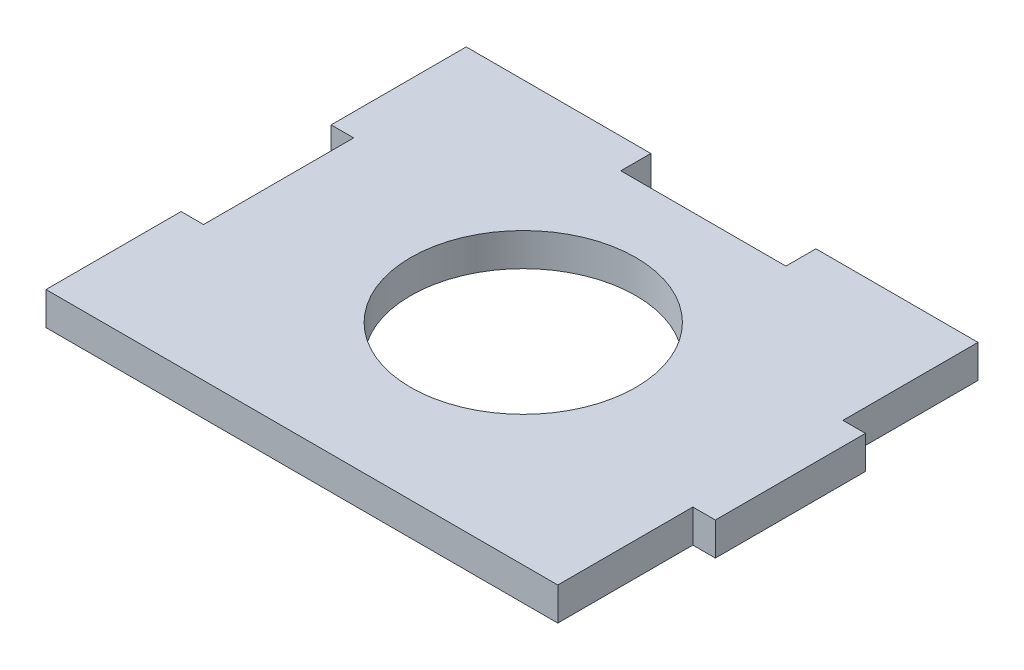
SolidWorks part; units mm, degrees
material "cardboard"
ref_plane "Front Plane" through (0, 0, 0) normal (0, 0, 1) x (1, 0, 0)
ref_plane "Top Plane" through (0, 0, 0) normal (0, 1, 0) x (1, 0, 0)
ref_plane "Right Plane" through (0, 0, 0) normal (1, 0, 0) x (0, 0, -1)
sketch "Sketch1" plane through (0, 0, 0) normal (0, 1, 0) x (1, 0, 0)
  line L0 (-131.9046, 127.7058) -> (-120.9046, 127.7058)
  line L1 (-121.9046, 123.7058) -> (-121.9046, 107.7058)
  line L2 (-62.1046, 123.7058) -> (-62.1046, 107.7058)
  line L3 (-119.5046, 107.7058) -> (-121.9046, 107.7058)
  line L4 (-133.3046, 123.7058) -> (-130.9046, 123.7058)
  line L5 (-133.3046, 123.7058) -> (-133.3046, 107.7058)
  line L6 (-133.3046, 107.7058) -> (-130.9046, 107.7058)
  line L7 (-130.9046, 123.7058) -> (-130.9046, 107.7058)
  line L8 (-119.5046, 123.7058) -> (-119.5046, 107.7058)
  line L9 (-119.5046, 123.7058) -> (-121.9046, 123.7058)
  line L10 (-59.7046, 123.7058) -> (-59.7046, 107.7058)
  line L11 (-96.3046, 127.7058) -> (-85.3046, 127.7058)
  line L12 (-62.1046, 123.7058) -> (-59.7046, 123.7058)
  line L13 (-62.1046, 107.7058) -> (-59.7046, 107.7058)
  line L14 (-50.7046, 123.7058) -> (-50.7046, 107.7058)
  line L15 (-48.3046, 123.7058) -> (-50.7046, 123.7058)
  line L16 (-48.3046, 123.7058) -> (-48.3046, 107.7058)
  line L17 (-48.3046, 107.7058) -> (-50.7046, 107.7058)
  line L18 (9.0954, 123.7058) -> (9.0954, 107.7058)
  line L19 (11.4954, 123.7058) -> (11.4954, 107.7058)
  line L20 (9.0954, 123.7058) -> (11.4954, 123.7058)
  line L21 (9.0954, 107.7058) -> (11.4954, 107.7058)
  line L22 (20.4954, 123.7058) -> (20.4954, 107.7058)
  line L23 (22.8954, 123.7058) -> (20.4954, 123.7058)
  line L24 (22.8954, 123.7058) -> (22.8954, 107.7058)
  line L25 (22.8954, 107.7058) -> (20.4954, 107.7058)
  line L26 (80.2954, 123.7058) -> (80.2954, 107.7058)
  line L27 (82.6954, 123.7058) -> (82.6954, 107.7058)
  line L28 (-60.7046, 127.7058) -> (-49.7046, 127.7058)
  line L29 (80.2954, 123.7058) -> (82.6954, 123.7058)
  line L30 (80.2954, 107.7058) -> (82.6954, 107.7058)
  line L31 (91.6954, 123.7058) -> (91.6954, 107.7058)
  line L32 (57.0954, 129.7058) -> (81.6954, 129.7058)
  line L33 (94.0954, 123.7058) -> (91.6954, 123.7058)
  line L34 (94.0954, 123.7058) -> (94.0954, 107.7058)
  line L35 (94.0954, 107.7058) -> (91.6954, 107.7058)
  line L36 (63.1525, 37.6692) -> (69.5684, 31.2534)
  line L37 (83.0553, 17.7664) -> (85.0352, 19.7463)
  line L38 (63.1525, 37.6692) -> (65.1324, 39.6491)
  line L39 (76.6394, 24.1823) -> (83.0553, 17.7664)
  line L40 (83.0553, -85.0845) -> (76.6394, -91.5004)
  line L41 (83.0553, -85.0845) -> (85.0352, -87.0644)
  line L42 (85.0352, -87.0644) -> (65.1324, -106.9672)
  line L43 (63.1525, -104.9873) -> (65.1324, -106.9672)
  line L44 (69.5684, -98.5714) -> (63.1525, -104.9873)
  line L45 (-39.6984, -104.9873) -> (-46.1143, -98.5714)
  line L46 (-39.6984, -104.9873) -> (-41.6783, -106.9672)
  line L47 (-41.6783, -106.9672) -> (-61.5811, -87.0644)
  line L48 (-59.6012, -85.0845) -> (-61.5811, -87.0644)
  line L49 (-53.1854, -91.5004) -> (-59.6012, -85.0845)
  line L50 (-25.1046, 127.7058) -> (-14.1046, 127.7058)
  line L51 (10.4954, 127.7058) -> (21.4954, 127.7058)
  line L52 (46.0954, 127.7058) -> (57.0954, 127.7058)
  line L53 (81.6954, 127.7058) -> (92.6954, 127.7058)
  line L54 (117.2954, 127.7058) -> (128.2954, 127.7058)
  line L55 (-36.375, -101.6639) -> (-34.3056, -103.7333)
  line L56 (-5.9695, -75.501) -> (-3.9, -77.5704)
  line L57 (-56.2778, -81.7611) -> (-58.0456, -83.5289)
  line L58 (-36.375, -101.6639) -> (-38.1428, -103.4317)
  line L59 (-32.1843, -49.2861) -> (-58.3473, -75.4491)
  line L60 (-58.3473, -79.6917) -> (-56.2778, -81.7611)
  line L61 (-3.9, -77.5704) -> (-30.063, -103.7333)
  line L62 (-32.1843, -49.2861) -> (-30.1149, -51.3555)
  line L63 (-144.2046, 129.7058) -> (-131.9046, 129.7058)
  line L64 (-55.5889, 82.4075) -> (-55.5889, 87.4075)
  line L65 (-65.5889, 82.4075) -> (-65.5889, 87.4075)
  line L66 (-35.039, 73.8955) -> (-31.5034, 77.431)
  line L67 (-27.9679, 66.8244) -> (-24.4324, 70.3599)
  line L68 (-19.4559, 46.2745) -> (-14.4559, 46.2745)
  line L69 (-19.4559, 36.2745) -> (-14.4559, 36.2745)
  line L70 (-27.9679, 15.7246) -> (-24.4324, 12.189)
  line L71 (-35.039, 8.6535) -> (-31.5034, 5.118)
  line L72 (-55.5889, 0.1414) -> (-55.5889, -4.8586)
  line L73 (-65.5889, 0.1414) -> (-65.5889, -4.8586)
  line L74 (-86.1388, 8.6535) -> (-89.6743, 5.118)
  line L75 (61.5969, 36.1136) -> (68.0127, 29.6977)
  line L76 (75.0838, 22.6267) -> (81.4997, 16.2108)
  line L77 (75.0838, 22.6267) -> (76.6394, 24.1823)
  line L78 (68.0127, 29.6977) -> (69.5684, 31.2534)
  line L79 (29.8004, -77.2921) -> (32.6289, -74.4636)
  line L80 (55.3601, -15.5856) -> (52.5316, -12.7572)
  line L81 (-144.2046, 129.7058) -> (-144.2046, 119.7058)
  line L82 (-6.3464, 9.974) -> (-31.906, -15.5856)
  line L83 (-144.2046, 101.7058) -> (-110.1046, 101.7058)
  line L84 (-93.2099, 15.7246) -> (-96.7454, 12.189)
  line L85 (-108.6046, 129.7058) -> (-108.6046, 120.7058)
  line L86 (65.1324, 39.6491) -> (85.0352, 19.7463)
  line L87 (-22.6903, -48.1735) -> (-2.7875, -68.0763)
  line L88 (-22.6903, -48.1735) -> (-25.8722, -51.3555)
  line L89 (-2.7875, -68.0763) -> (-5.9695, -71.2583)
  line L90 (-31.906, -15.5856) -> (-66.906, -15.5856)
  line L91 (-81.906, -30.5856) -> (-81.906, -36.7324)
  line L92 (-66.906, -51.7324) -> (-34.6306, -51.7324)
  line L93 (-111.9046, 106.7058) -> (-114.4046, 106.7058)
  line L94 (-140.9046, 126.7058) -> (-138.4046, 126.7058)
  line L95 (-140.9046, 126.7058) -> (-140.9046, 106.7058)
  line L96 (-140.9046, 106.7058) -> (-138.4046, 106.7058)
  line L97 (-138.4046, 126.7058) -> (-138.4046, 106.7058)
  line L98 (-114.4046, 126.7058) -> (-114.4046, 106.7058)
  line L99 (29.8004, 9.974) -> (29.8004, 44.974)
  line L100 (14.8004, 59.974) -> (8.6536, 59.974)
  line L101 (-6.3464, 44.974) -> (-6.3464, 9.974)
  line L102 (-111.9046, 126.7058) -> (-114.4046, 126.7058)
  line L103 (-111.9046, 126.7058) -> (-111.9046, 106.7058)
  line L104 (-132.4046, 101.7058) -> (-132.4046, 97.7058)
  line L105 (-132.4046, 97.7058) -> (-120.4046, 97.7058)
  line L106 (-120.4046, 97.7058) -> (-120.4046, 101.7058)
  line L107 (-108.6046, 129.7058) -> (-108.6046, 120.7058)
  line L108 (55.3601, -51.7324) -> (90.3601, -51.7324)
  line L109 (105.3601, -36.7324) -> (105.3601, -30.5856)
  line L110 (90.3601, -15.5856) -> (55.3601, -15.5856)
  line L111 (-108.6046, 101.7058) -> (-74.5046, 101.7058)
  line L112 (-73.0046, 120.7058) -> (-73.0046, 110.7058)
  line L113 (21.4954, 129.7058) -> (46.0954, 129.7058)
  line L114 (-73.0046, 120.7058) -> (-73.0046, 110.7058)
  line L115 (-61.2046, 101.7058) -> (-37.4046, 101.7058)
  line L116 (-37.4046, 129.7058) -> (-37.4046, 101.7058)
  line L117 (-6.3464, -80.0167) -> (-6.3464, -112.2921)
  line L118 (8.6536, -127.2921) -> (14.8004, -127.2921)
  line L119 (29.8004, -112.2921) -> (29.8004, -77.2921)
  line L120 (-14.1046, 129.7058) -> (10.4954, 129.7058)
  line L121 (-37.4046, 129.7058) -> (-37.4046, 101.7058)
  line L122 (-37.4046, 101.7058) -> (-1.8046, 101.7058)
  line L123 (-1.8046, 129.7058) -> (-1.8046, 101.7058)
  line L124 (-49.7046, 129.7058) -> (-25.1046, 129.7058)
  line L125 (-1.8046, 129.7058) -> (-1.8046, 101.7058)
  line L126 (52.5316, -54.5609) -> (55.3601, -51.7324)
  line L127 (26.2415, -68.0763) -> (46.1443, -48.1735)
  line L128 (81.4997, -83.5289) -> (75.0838, -89.9447)
  line L129 (46.1443, -48.1735) -> (81.4997, -83.5289)
  line L130 (75.0838, -89.9447) -> (76.6394, -91.5004)
  line L131 (78.6193, -93.4803) -> (71.5483, -100.5513)
  line L132 (26.2415, -68.0763) -> (61.5969, -103.4317)
  line L133 (68.0127, -97.0158) -> (69.5684, -98.5714)
  line L134 (68.0127, -97.0158) -> (61.5969, -103.4317)
  line L135 (-38.1428, -103.4317) -> (-44.5587, -97.0158)
  line L136 (-44.5587, -97.0158) -> (-46.1143, -98.5714)
  line L137 (32.6289, 7.1456) -> (29.8004, 9.974)
  line L138 (-101.7219, 36.2745) -> (-106.7219, 36.2745)
  line L139 (46.1443, -19.1445) -> (26.2415, 0.7582)
  line L140 (46.1443, -19.1445) -> (81.4997, 16.2108)
  line L141 (26.2415, 0.7582) -> (61.5969, 36.1136)
  line L142 (-48.0942, -100.5513) -> (-55.1653, -93.4803)
  line L143 (-51.6297, -89.9447) -> (-53.1854, -91.5004)
  line L144 (-51.6297, -89.9447) -> (-58.0456, -83.5289)
  line L145 (-65.5889, 82.4075) -> (-77.6267, 82.4075)
  line L146 (-77.6267, 82.4075) -> (-86.1388, 73.8955)
  line L147 (-1.8046, 101.7058) -> (33.7954, 101.7058)
  line L148 (33.7954, 129.7058) -> (33.7954, 101.7058)
  line L149 (-85.3046, 129.7058) -> (-74.5046, 129.7058)
  line L150 (33.7954, 129.7058) -> (33.7954, 101.7058)
  line L151 (33.7954, 101.7058) -> (69.3954, 101.7058)
  line L152 (69.3954, 129.7058) -> (69.3954, 101.7058)
  line L153 (-108.6046, 129.7058) -> (-96.3046, 129.7058)
  line L154 (69.3954, 129.7058) -> (69.3954, 101.7058)
  line L155 (69.3954, 101.7058) -> (104.9954, 101.7058)
  line L156 (104.9954, 129.7058) -> (104.9954, 101.7058)
  line L157 (128.2954, 129.7058) -> (140.5954, 129.7058)
  line L158 (104.9954, 129.7058) -> (104.9954, 101.7058)
  line L159 (104.9954, 101.7058) -> (140.5954, 101.7058)
  line L160 (140.5954, 129.7058) -> (140.5954, 119.7058)
  line L161 (-69.7046, 126.7058) -> (-67.2046, 126.7058)
  line L162 (-69.7046, 126.7058) -> (-69.7046, 106.7058)
  line L163 (-69.7046, 106.7058) -> (-67.2046, 106.7058)
  line L164 (-67.2046, 126.7058) -> (-67.2046, 106.7058)
  line L165 (-43.2046, 126.7058) -> (-43.2046, 106.7058)
  line L166 (-40.7046, 106.7058) -> (-43.2046, 106.7058)
  line L167 (-40.7046, 126.7058) -> (-40.7046, 106.7058)
  line L168 (-40.7046, 126.7058) -> (-43.2046, 126.7058)
  line L169 (-61.2046, 101.7058) -> (-61.2046, 97.7058)
  line L170 (-61.2046, 97.7058) -> (-49.2046, 97.7058)
  line L171 (-49.2046, 97.7058) -> (-49.2046, 101.7058)
  line L172 (1.4954, 126.7058) -> (3.9954, 126.7058)
  line L173 (1.4954, 126.7058) -> (1.4954, 106.7058)
  line L174 (1.4954, 106.7058) -> (3.9954, 106.7058)
  line L175 (3.9954, 126.7058) -> (3.9954, 106.7058)
  line L176 (27.9954, 126.7058) -> (27.9954, 106.7058)
  line L177 (30.4954, 106.7058) -> (27.9954, 106.7058)
  line L178 (30.4954, 126.7058) -> (30.4954, 106.7058)
  line L179 (30.4954, 126.7058) -> (27.9954, 126.7058)
  line L180 (9.9954, 101.7058) -> (9.9954, 97.7058)
  line L181 (9.9954, 97.7058) -> (21.9954, 97.7058)
  line L182 (21.9954, 97.7058) -> (21.9954, 101.7058)
  line L183 (72.6954, 126.7058) -> (75.1954, 126.7058)
  line L184 (72.6954, 126.7058) -> (72.6954, 106.7058)
  line L185 (72.6954, 106.7058) -> (75.1954, 106.7058)
  line L186 (75.1954, 126.7058) -> (75.1954, 106.7058)
  line L187 (99.1954, 126.7058) -> (99.1954, 106.7058)
  line L188 (101.6954, 106.7058) -> (99.1954, 106.7058)
  line L189 (101.6954, 126.7058) -> (101.6954, 106.7058)
  line L190 (101.6954, 126.7058) -> (99.1954, 126.7058)
  line L191 (81.1954, 101.7058) -> (81.1954, 97.7058)
  line L192 (81.1954, 97.7058) -> (93.1954, 97.7058)
  line L193 (93.1954, 97.7058) -> (93.1954, 101.7058)
  line L194 (-132.4046, 100.7058) -> (-128.4046, 100.7058)
  line L195 (-128.4046, 100.7058) -> (-128.4046, 102.7058)
  line L196 (-128.4046, 102.7058) -> (-124.4046, 102.7058)
  line L197 (-124.4046, 102.7058) -> (-124.4046, 100.7058)
  line L198 (-124.4046, 100.7058) -> (-120.4046, 100.7058)
  line L199 (-61.2046, 100.7058) -> (-57.2046, 100.7058)
  line L200 (-57.2046, 100.7058) -> (-57.2046, 102.7058)
  line L201 (-57.2046, 102.7058) -> (-53.2046, 102.7058)
  line L202 (-53.2046, 102.7058) -> (-53.2046, 100.7058)
  line L203 (-53.2046, 100.7058) -> (-49.2046, 100.7058)
  line L204 (9.9954, 100.7058) -> (13.9954, 100.7058)
  line L205 (13.9954, 100.7058) -> (13.9954, 102.7058)
  line L206 (13.9954, 102.7058) -> (17.9954, 102.7058)
  line L207 (27.6557, 2.1725) -> (34.0197, -4.1915)
  line L208 (34.0197, -4.1915) -> (31.1913, -7.0199)
  line L209 (31.1913, -7.0199) -> (38.3661, -14.1948)
  line L210 (38.3661, -14.1948) -> (41.1946, -11.3664)
  line L211 (41.1946, -11.3664) -> (47.5585, -17.7303)
  line L212 (47.5585, -49.5878) -> (41.1946, -55.9517)
  line L213 (41.1946, -55.9517) -> (38.3661, -53.1233)
  line L214 (38.3661, -53.1233) -> (31.1913, -60.2982)
  line L215 (31.1913, -60.2982) -> (34.0197, -63.1266)
  line L216 (34.0197, -63.1266) -> (27.6557, -69.4905)
  line L217 (-4.2017, -69.4905) -> (-10.5656, -63.1266)
  line L218 (-10.5656, -63.1266) -> (-7.7372, -60.2982)
  line L219 (-7.7372, -60.2982) -> (-14.9121, -53.1233)
  line L220 (-14.9121, -53.1233) -> (-17.7405, -55.9517)
  line L221 (-17.7405, -55.9517) -> (-24.1045, -49.5878)
  line L222 (-89.6743, 77.431) -> (-96.7454, 70.3599)
  line L223 (-93.2099, 66.8244) -> (-101.7219, 58.3123)
  line L224 (-101.7219, 58.3123) -> (-101.7219, 46.2745)
  line L225 (-106.7219, 46.2745) -> (-106.7219, 36.2745)
  line L226 (-101.7219, 36.2745) -> (-101.7219, 24.2366)
  line L227 (-101.7219, 24.2366) -> (-93.2099, 15.7246)
  line L228 (-96.7454, 12.189) -> (-89.6743, 5.118)
  line L229 (-86.1388, 8.6535) -> (-77.6267, 0.1414)
  line L230 (-77.6267, 0.1414) -> (-65.5889, 0.1414)
  line L231 (-65.5889, -4.8586) -> (-55.5889, -4.8586)
  line L232 (-55.5889, 0.1414) -> (-43.551, 0.1414)
  line L233 (-43.551, 0.1414) -> (-35.039, 8.6535)
  line L234 (-31.5034, 5.118) -> (-24.4324, 12.189)
  line L235 (-27.9679, 15.7246) -> (-19.4559, 24.2366)
  line L236 (-19.4559, 24.2366) -> (-19.4559, 36.2745)
  line L237 (-14.4559, 36.2745) -> (-14.4559, 46.2745)
  line L238 (-19.4559, 46.2745) -> (-19.4559, 58.3123)
  line L239 (-19.4559, 58.3123) -> (-27.9679, 66.8244)
  line L240 (-24.4324, 70.3599) -> (-31.5034, 77.431)
  line L241 (-35.039, 73.8955) -> (-43.551, 82.4075)
  line L242 (-43.551, 82.4075) -> (-55.5889, 82.4075)
  line L243 (-55.5889, 87.4075) -> (-65.5889, 87.4075)
  line L244 (-101.7219, 46.2745) -> (-106.7219, 46.2745)
  line L245 (-93.2099, 66.8244) -> (-96.7454, 70.3599)
  line L246 (-86.1388, 73.8955) -> (-89.6743, 77.431)
  line L247 (17.9954, 102.7058) -> (17.9954, 100.7058)
  line L248 (17.9954, 100.7058) -> (21.9954, 100.7058)
  line L249 (81.1954, 100.7058) -> (85.1954, 100.7058)
  line L250 (85.1954, 100.7058) -> (85.1954, 102.7058)
  line L251 (85.1954, 102.7058) -> (89.1954, 102.7058)
  line L252 (89.1954, 102.7058) -> (89.1954, 100.7058)
  line L253 (89.1954, 100.7058) -> (93.1954, 100.7058)
  line L254 (140.5954, 119.7058) -> (142.5954, 119.7058)
  line L255 (142.5954, 111.7058) -> (140.5954, 111.7058)
  line L256 (140.5954, 111.7058) -> (140.5954, 101.7058)
  line L257 (-144.2046, 119.7058) -> (-143.2046, 119.7058)
  line L258 (-143.2046, 119.7058) -> (-143.2046, 111.7058)
  line L259 (-143.2046, 111.7058) -> (-144.2046, 111.7058)
  line L260 (-144.2046, 111.7058) -> (-144.2046, 101.7058)
  line L262 (-108.6046, 120.7058) -> (-107.1046, 120.7058)
  line L263 (-107.1046, 120.7058) -> (-107.1046, 110.7058)
  line L264 (-107.1046, 110.7058) -> (-108.6046, 110.7058)
  line L265 (-108.6046, 110.7058) -> (-108.6046, 101.7058)
  line L266 (-74.5046, 129.7058) -> (-74.5046, 120.7058)
  line L267 (-74.5046, 120.7058) -> (-73.0046, 120.7058)
  line L268 (-108.6046, 110.7058) -> (-108.6046, 101.7058)
  line L269 (-73.0046, 110.7058) -> (-74.5046, 110.7058)
  line L270 (-74.5046, 110.7058) -> (-74.5046, 101.7058)
  line L271 (-38.9046, 129.7058) -> (-38.9046, 120.7058)
  line L272 (-38.9046, 120.7058) -> (-35.9046, 120.7058)
  line L273 (-35.9046, 120.7058) -> (-35.9046, 110.7058)
  line L274 (-35.9046, 110.7058) -> (-38.9046, 110.7058)
  line L275 (-38.9046, 110.7058) -> (-38.9046, 101.7058)
  line L276 (-3.3046, 129.7058) -> (-3.3046, 120.7058)
  line L277 (-3.3046, 120.7058) -> (-0.3046, 120.7058)
  line L278 (-0.3046, 120.7058) -> (-0.3046, 110.7058)
  line L279 (-0.3046, 110.7058) -> (-3.3046, 110.7058)
  line L280 (-3.3046, 110.7058) -> (-3.3046, 101.7058)
  line L281 (32.2954, 129.7058) -> (32.2954, 120.7058)
  line L282 (32.2954, 120.7058) -> (35.2954, 120.7058)
  line L283 (35.2954, 120.7058) -> (35.2954, 110.7058)
  line L284 (35.2954, 110.7058) -> (32.2954, 110.7058)
  line L285 (32.2954, 110.7058) -> (32.2954, 101.7058)
  line L286 (67.8954, 129.7058) -> (67.8954, 120.7058)
  line L287 (67.8954, 120.7058) -> (70.8954, 120.7058)
  line L288 (70.8954, 120.7058) -> (70.8954, 110.7058)
  line L289 (70.8954, 110.7058) -> (67.8954, 110.7058)
  line L290 (67.8954, 110.7058) -> (67.8954, 101.7058)
  line L291 (103.4954, 129.7058) -> (103.4954, 120.7058)
  line L292 (103.4954, 120.7058) -> (106.4954, 120.7058)
  line L293 (106.4954, 120.7058) -> (106.4954, 110.7058)
  line L294 (106.4954, 110.7058) -> (103.4954, 110.7058)
  line L295 (103.4954, 110.7058) -> (103.4954, 101.7058)
  line L296 (142.5954, 119.7058) -> (142.5954, 111.7058)
  line L297 (-131.9046, 129.7058) -> (-131.9046, 127.7058)
  line L298 (-120.9046, 129.7058) -> (-120.9046, 127.7058)
  line L299 (-96.3046, 129.7058) -> (-96.3046, 127.7058)
  line L300 (-85.3046, 129.7058) -> (-85.3046, 127.7058)
  line L301 (-60.7046, 129.7058) -> (-60.7046, 127.7058)
  line L302 (-49.7046, 129.7058) -> (-49.7046, 127.7058)
  line L303 (-25.1046, 129.7058) -> (-25.1046, 127.7058)
  line L304 (-14.1046, 129.7058) -> (-14.1046, 127.7058)
  line L305 (10.4954, 129.7058) -> (10.4954, 127.7058)
  line L306 (21.4954, 129.7058) -> (21.4954, 127.7058)
  line L307 (46.0954, 129.7058) -> (46.0954, 127.7058)
  line L308 (57.0954, 129.7058) -> (57.0954, 127.7058)
  line L309 (81.6954, 129.7058) -> (81.6954, 127.7058)
  line L310 (92.6954, 129.7058) -> (92.6954, 127.7058)
  line L311 (117.2954, 129.7058) -> (117.2954, 127.7058)
  line L312 (128.2954, 129.7058) -> (128.2954, 127.7058)
  line L313 (92.6954, 129.7058) -> (117.2954, 129.7058)
  line L314 (-73.0046, 129.7058) -> (-60.7046, 129.7058)
  circle A0 centre (-32.1843, -56.3572) radius 1.75
  circle A1 centre (-60.5889, 68.2745) radius 6
  circle A2 centre (-41.497, 60.3664) radius 6
  circle A3 centre (-33.5889, 41.2745) radius 6
  circle A4 centre (-10.9711, -77.5704) radius 1.75
  circle A5 centre (-32.1843, -98.7836) radius 1.75
  circle A6 centre (11.727, 34.974) radius 10
  circle A7 centre (-126.4046, 114.2058) radius 1
  circle A8 centre (-53.3975, -77.5704) radius 1.75
  arc A9 (-30.1149, -51.3555) -> (-25.8722, -51.3555) centre (-27.9936, -49.2342) ccw
  arc A10 (-5.9695, -75.501) -> (-5.9695, -71.2583) centre (-3.8481, -73.3796) cw
  circle A11 centre (-55.2046, 114.2058) radius 1
  circle A12 centre (80.3601, -33.659) radius 10
  circle A13 centre (11.727, -33.659) radius 15
  arc A14 (-66.906, -15.5856) -> (-81.906, -30.5856) centre (-66.906, -30.5856) ccw
  arc A15 (-81.906, -36.7324) -> (-66.906, -51.7324) centre (-66.906, -36.7324) ccw
  arc A16 (-6.3464, -112.2921) -> (8.6536, -127.2921) centre (8.6536, -112.2921) ccw
  arc A17 (14.8004, -127.2921) -> (29.8004, -112.2921) centre (14.8004, -112.2921) ccw
  arc A18 (90.3601, -51.7324) -> (105.3601, -36.7324) centre (90.3601, -36.7324) ccw
  arc A19 (105.3601, -30.5856) -> (90.3601, -15.5856) centre (90.3601, -30.5856) ccw
  arc A20 (29.8004, 44.974) -> (14.8004, 59.974) centre (14.8004, 44.974) ccw
  circle A21 centre (15.9954, 114.2058) radius 1
  circle A22 centre (11.727, -102.2921) radius 10
  circle A23 centre (87.1954, 114.2058) radius 1
  circle A24 centre (-56.906, -33.659) radius 10
  circle A25 centre (-41.497, 22.1826) radius 6
  circle A26 centre (-90.8046, 115.7058) radius 7.5
  circle A27 centre (-19.6046, 115.7058) radius 7.5
  circle A28 centre (51.5954, 115.7058) radius 7.5
  circle A29 centre (122.7954, 115.7058) radius 7.5
  arc A30 (8.6536, 59.974) -> (-6.3464, 44.974) centre (8.6536, 44.974) ccw
  arc A31 (-34.3056, -103.7333) -> (-30.063, -103.7333) centre (-32.1843, -101.612) ccw
  arc A32 (-58.3473, -75.4491) -> (-58.3473, -79.6917) centre (-56.2259, -77.5704) ccw
  circle A33 centre (-60.5889, 14.2745) radius 6
  circle A34 centre (-79.6808, 22.1826) radius 6
  circle A35 centre (-87.5889, 41.2745) radius 6
  circle A36 centre (-79.6808, 60.3664) radius 6
  circle A37 centre (-60.5889, 41.2745) radius 15
  point P64 (11.727, -33.659)
  point P110 (11.727, -33.659)
  point P169 (11.727, -33.659)
  point P171 (11.727, -33.659)
  point P181 (11.727, -33.659)
  point P187 (11.727, -33.659)
  point P251 (11.727, -33.659)
  point P273 (11.727, -33.659)
  point P284 (11.727, -33.659)
  point P318 (-60.5889, 41.2745)
  point P319 (-60.5889, 41.2745)
  point P408 (-60.5889, 41.2745)
extrude "Boss-Extrude1" add sketch "Sketch1" along normal blind 2.2 contours L149 L300 L11 L299 L153 L85 L262 L263 L264 L265 L111 L270 L269 L112 L267 L266 A26
